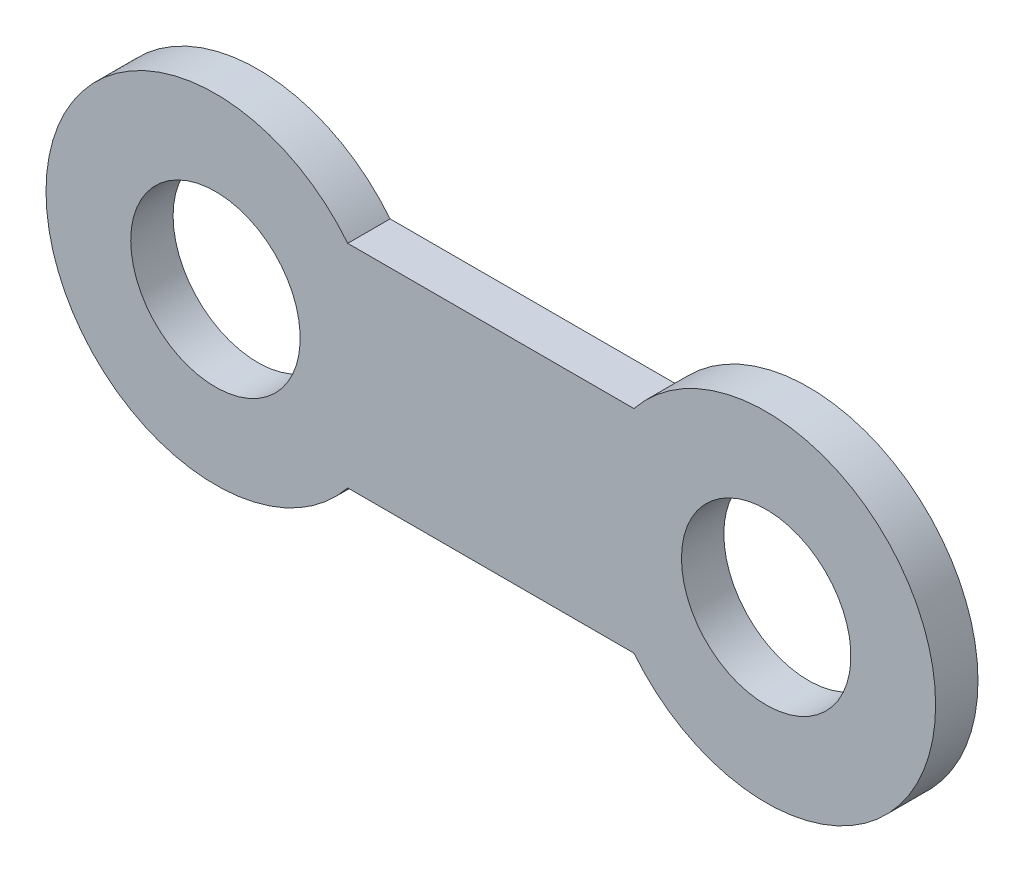
SolidWorks part; units mm, degrees
ref_plane "前视基准面" through (0, 0, 0) normal (0, 0, 1) x (1, 0, 0)
ref_plane "上视基准面" through (0, 0, 0) normal (0, 1, 0) x (1, 0, 0)
ref_plane "右视基准面" through (0, 0, 0) normal (1, 0, 0) x (0, 0, -1)
sketch "草图1" plane through (0, 0, 0) normal (0, 0, 1) x (1, 0, 0)
  line L1 (-42.5, -12.5) -> (42.5, -12.5)
  line L2 (-42.5, -12.5) -> (-42.5, 12.5)
  line L3 (-42.5, 12.5) -> (42.5, 12.5)
  line L4 (42.5, -12.5) -> (42.5, 12.5)
  line L5 (-42.5, -12.5) -> (42.5, 12.5) construction
  line L6 (-42.5, 12.5) -> (42.5, -12.5) construction
  point P0 (0, 0)
  dimension "D1" = 25
  dimension "D2" = 85
extrude "凸台-拉伸1" add sketch "草图1" along normal blind 5
sketch "草图2" plane through (0, 0, 5) normal (0, 0, 1) x (1, 0, 0)
  line L0 (-32.5, 0) -> (32.5, 0) construction
  circle A0 centre (32.5, 0) radius 20
  circle A1 centre (-32.5, 0) radius 20
  point P4 (0, 0)
  dimension "D2" = 40
  dimension "D1" = 65
extrude "凸台-拉伸2" add sketch "草图2" against normal up to surface (5 mm away) up to face at (0, 0, 0)
sketch "草图3" plane through (0, 0, 0) normal (0, 0, -1) x (-1, 0, 0)
  circle A0 centre (-32.5, 0) radius 10
  circle A1 centre (32.5, 0) radius 10
  dimension "D1" = 20
extrude "切除-拉伸1" cut sketch "草图3" against normal blind 35
